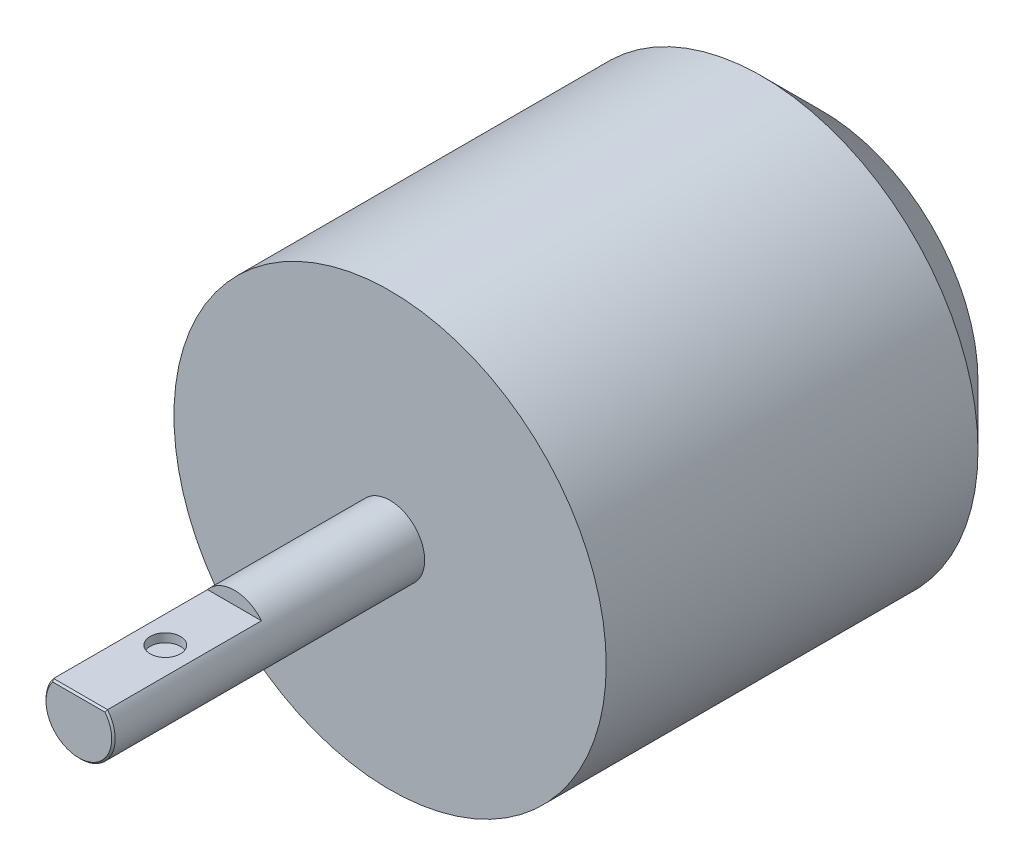
SolidWorks part; units mm, degrees
ref_plane "前视基准面" through (0, 0, 0) normal (0, 0, 1) x (1, 0, 0)
ref_plane "上视基准面" through (0, 0, 0) normal (0, 1, 0) x (1, 0, 0)
ref_plane "右视基准面" through (0, 0, 0) normal (1, 0, 0) x (0, 0, -1)
sketch "草图1" plane through (0, 0, 0) normal (0, 0, 1) x (1, 0, 0)
  circle A0 centre (0, 0) radius 25
  dimension "D1" = 50
extrude "凸台-拉伸1" add sketch "草图1" along normal blind 50
chamfer "倒角1" distance 7 angle 45 1 edges at (25, 0, 0)
sketch "草图2" plane through (0, 0, 0) normal (0, 0, -1) x (-1, 0, 0)
  circle A0 centre (0, 0) radius 10
  dimension "D1" = 20
extrude "凸台-拉伸2" add sketch "草图2" along normal blind 1.5
sketch "草图3" plane through (0, 0, 50) normal (0, 0, 1) x (1, 0, 0)
  circle A0 centre (0, 0) radius 4
  dimension "D1" = 8
extrude "凸台-拉伸3" add sketch "草图3" along normal blind 36
sketch "草图4" plane through (0, 0, 86) normal (0, 0, 1) x (1, 0, 0)
  line L0 (-3.1225, 2.5) -> (3.1225, 2.5)
  line L1 (0, 0) -> (0, -4) construction
  circle A1 centre (0, 0) radius 4
  circle A2 centre (0, 0) radius 4
  circle M3 centre (0, 0) radius 4
  dimension "D2" = 6.5
  dimension "D1" = 0
extrude "切除-拉伸1" cut sketch "草图4" against normal blind 18 contours L0 M3
sketch "草图5" plane through (0, 2.5, 0) normal (0, 1, 0) x (1, 0, 0)
  line L0 (-3.1225, -86) -> (3.1225, -86) construction
  circle A0 centre (0, -76) radius 1.75
  dimension "D2" = 3.5
  dimension "D1" = 10
extrude "切除-拉伸2" cut sketch "草图5" against normal blind 1
chamfer "倒角2" distance 0.2 angle 45 2 edges at (0, -4, 86) (0, 2.5, 86)
